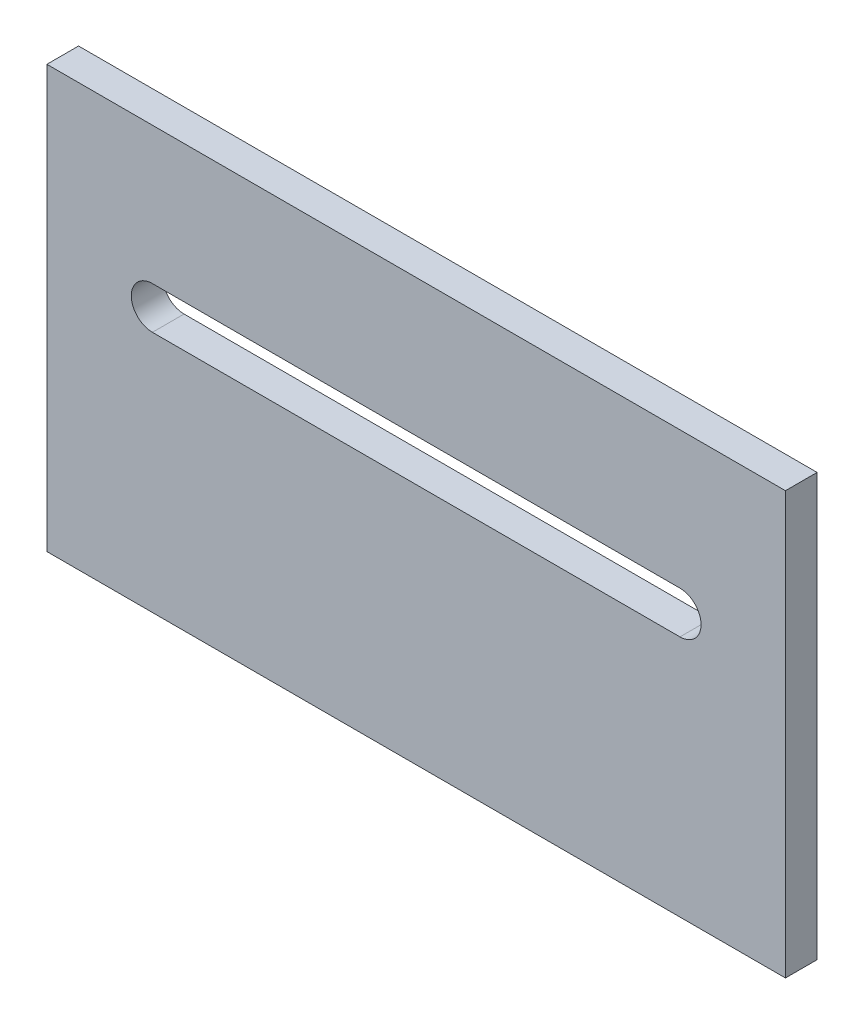
SolidWorks part; units mm, degrees
ref_plane "Front Plane" through (0, 0, 0) normal (0, 0, 1) x (1, 0, 0)
ref_plane "Top Plane" through (0, 0, 0) normal (0, 1, 0) x (1, 0, 0)
ref_plane "Right Plane" through (0, 0, 0) normal (1, 0, 0) x (0, 0, -1)
sketch "Sketch1" plane through (0, 0, 0) normal (0, 0, 1) x (1, 0, 0)
  line L1 (0, 0) -> (70, 0)
  line L2 (0, 0) -> (0, -40)
  line L3 (0, -40) -> (70, -40)
  line L4 (70, 0) -> (70, -40)
  dimension "D1" = 40
  dimension "D2" = 70
extrude "Boss-Extrude1" add sketch "Sketch1" along normal blind 3
sketch "Sketch2" plane through (0, 0, 3) normal (0, 0, 1) x (1, 0, 0)
  line L0 (10, -15) -> (60, -15) construction
  line L1 (10, -13) -> (60, -13)
  line L2 (10, -17) -> (60, -17)
  line L3 (0, 0) -> (0, -40) construction
  line L4 (0, -40) -> (70, -40) construction
  arc A0 (10, -13) -> (10, -17) centre (10, -15) ccw
  arc A1 (60, -17) -> (60, -13) centre (60, -15) ccw
  point P2 (35, -15)
  dimension "D1" = 2
  dimension "D2" = 50
  dimension "D3" = 10
  dimension "D4" = 25
extrude "Cut-Extrude1" cut sketch "Sketch2" against normal blind 3
